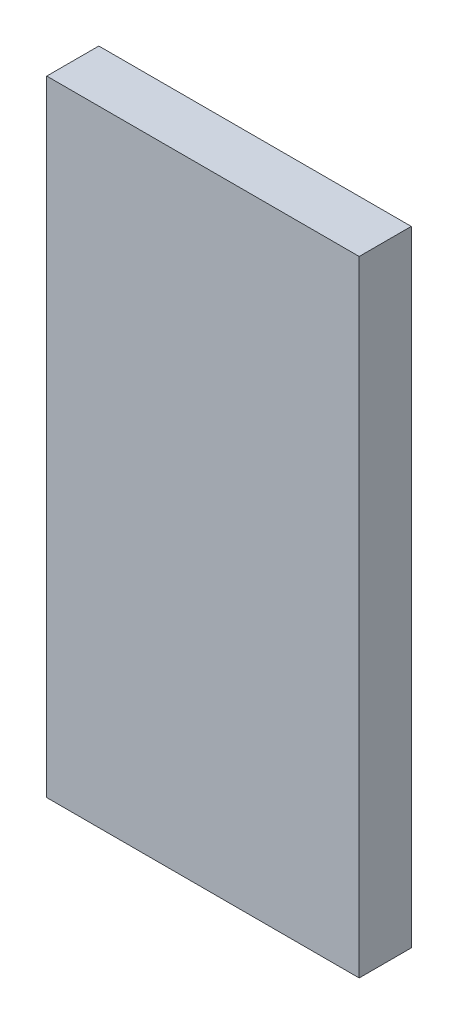
SolidWorks part; units mm, degrees
ref_plane "Front Plane" through (0, 0, 0) normal (0, 0, 1) x (1, 0, 0)
ref_plane "Top Plane" through (0, 0, 0) normal (0, 1, 0) x (1, 0, 0)
ref_plane "Right Plane" through (0, 0, 0) normal (1, 0, 0) x (0, 0, -1)
sketch "Sketch1" plane through (0, 0, 0) normal (0, 0, 1) x (1, 0, 0)
  line L1 (-76.2, -152.4) -> (76.2, -152.4)
  line L2 (-76.2, -152.4) -> (-76.2, 152.4)
  line L3 (-76.2, 152.4) -> (76.2, 152.4)
  line L4 (76.2, -152.4) -> (76.2, 152.4)
  line L5 (-76.2, -152.4) -> (76.2, 152.4) construction
  line L6 (-76.2, 152.4) -> (76.2, -152.4) construction
  point P0 (0, 0)
  dimension "D1" = 152.4
  dimension "D2" = 304.8
extrude "Boss-Extrude1" add sketch "Sketch1" along normal blind 25.4
